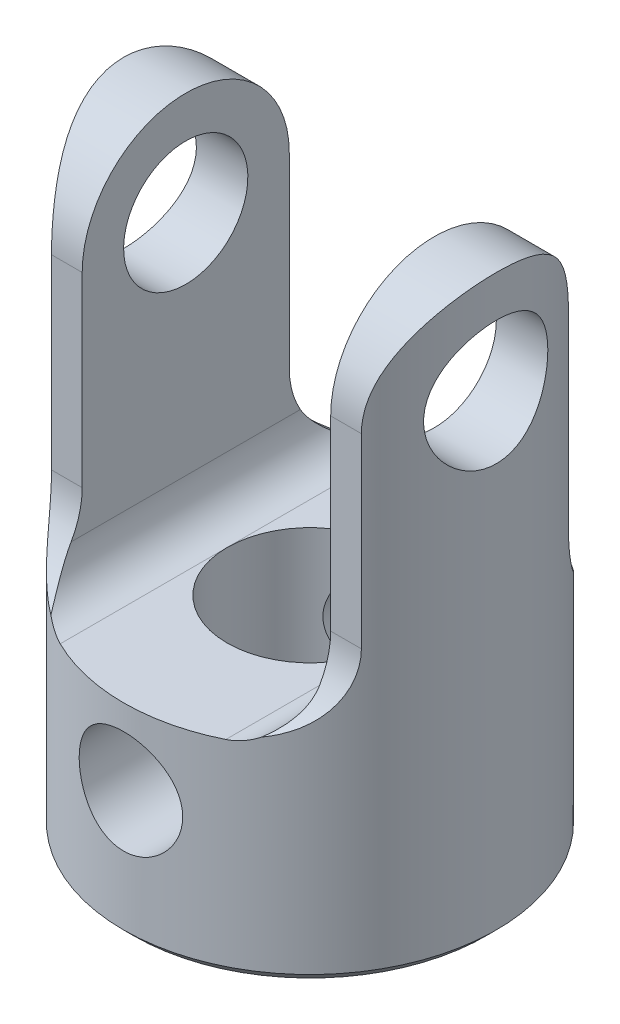
SolidWorks part; units mm, degrees
ref_plane "Front Plane" through (0, 0, 0) normal (0, 0, 1) x (1, 0, 0)
ref_plane "Top Plane" through (0, 0, 0) normal (0, 1, 0) x (1, 0, 0)
ref_plane "Right Plane" through (0, 0, 0) normal (1, 0, 0) x (0, 0, -1)
sketch "Sketch1" plane through (0, 0, 0) normal (0, 1, 0) x (1, 0, 0)
  circle A0 centre (0, 0) radius 4.5
  circle A1 centre (0, 0) radius 2
  dimension "D1" = 9
  dimension "D2" = 4
extrude "Boss-Extrude1" add sketch "Sketch1" along normal blind 14
sketch "Sketch2" plane through (0, 0, 0) normal (0, 0, 1) x (1, 0, 0)
  line L0 (4.5, 14) -> (-4.5, 14) construction
  line L1 (-3, 14) -> (3, 14)
  line L2 (-3, 14) -> (-3, 6)
  line L3 (-2, 5) -> (2, 5)
  line L4 (3, 14) -> (3, 6)
  line L5 (0, 3.15) -> (0, 0) construction
  line L7 (-4.5, 0) -> (4.5, 0) construction
  line L8 (-4.5, 14) -> (4.5, 14) construction
  arc A0 (2, 5) -> (3, 6) centre (2, 6) ccw
  arc A1 (-3, 6) -> (-2, 5) centre (-2, 6) ccw
  circle A2 centre (0, 3.15) radius 1.25
  point P16 (0, 14)
  point P17 (-2, 5)
  point P18 (0, 0)
  point P19 (0, 0)
  point P20 (0, 0)
  point P27 (3, 11.425)
  point P28 (2, 10.425)
  dimension "D3" = 1
  dimension "D4" = 2.5
  dimension "D5" = 4
  dimension "D1" = 6
  dimension "D2" = 3.15
  dimension "D6" = 8
extrude "Cut-Extrude1" cut sketch "Sketch2" against normal through all both and the other way through all
sketch "Sketch3" plane through (0, 0, 0) normal (1, 0, 0) x (0, 0, -1)
  line L0 (3.3541, 14) -> (-3.3541, 14) construction
  line L1 (2.5, 11.5) -> (2.5, 7)
  line L2 (-2.5, 11.5) -> (-2.5, 7)
  line L3 (0, 11.5) -> (0, 0) construction
  line L4 (4.5, 5) -> (4.5, 15)
  line L5 (4.5, 15) -> (-4.5, 15)
  line L6 (-4.5, 15) -> (-4.5, 5)
  line L9 (-4.5, 5) -> (4.5, 5) construction
  line L10 (4.5, 4.4) -> (4.5, 5) construction
  arc A0 (2.5, 11.5) -> (-2.5, 11.5) centre (0, 11.5) ccw
  arc A1 (-2.5, 7) -> (-4.5, 5) centre (-4.5, 7) cw
  arc A2 (2.5, 7) -> (4.5, 5) centre (4.5, 7) ccw
  circle A3 centre (0, 11.5) radius 1.5
  point P15 (0, 0)
  point P20 (-4.0825, 8.9559)
  dimension "D5" = 3
  dimension "D1" = 5
  dimension "D2" = 1
extrude "Cut-Extrude2" cut sketch "Sketch3" against normal through all both and the other way through all
chamfer "Chamfer1" distance 0.25 angle 45 1 edges at (0, 0, 4.5)
